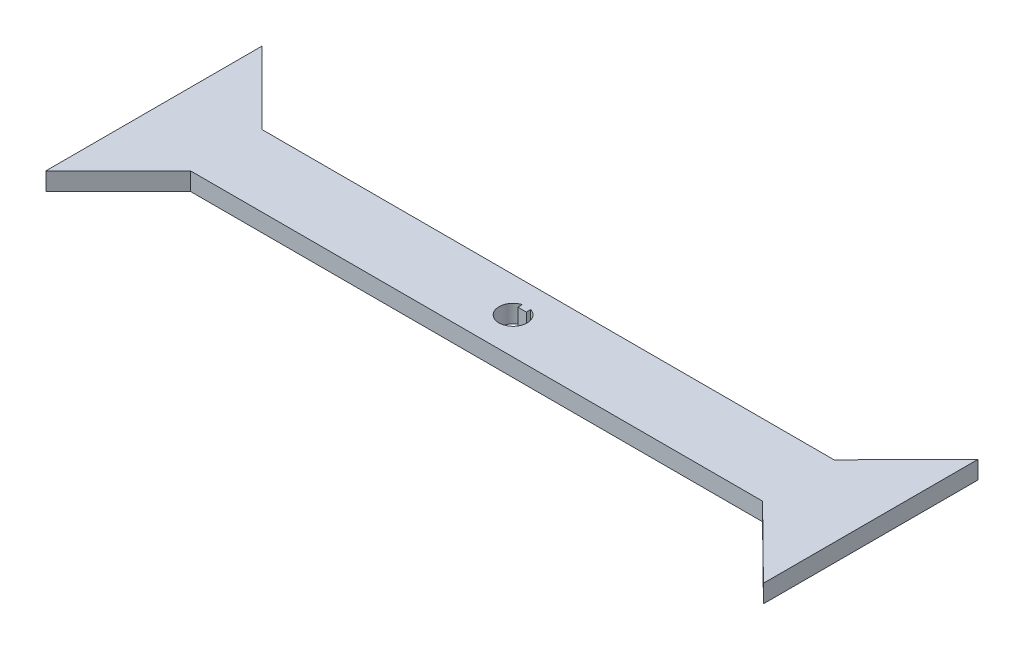
SolidWorks part; units mm, degrees
ref_plane "Front Plane" through (0, 0, 0) normal (0, 0, 1) x (1, 0, 0)
ref_plane "Top Plane" through (0, 0, 0) normal (0, 1, 0) x (1, 0, 0)
ref_plane "Right Plane" through (0, 0, 0) normal (1, 0, 0) x (0, 0, -1)
sketch "Sketch1" plane through (0, 0, 0) normal (0, 1, 0) x (1, 0, 0)
  line L0 (0, 25.4) -> (0, 51.0293)
  line L2 (0, 0) -> (0, 25.4)
  line L4 (254.2293, 0.3053) -> (254.2293, 25.7053)
  line L5 (0, 51.0293) -> (25.6293, 25.4)
  line L6 (0, 0) -> (0, -25.6293)
  line L7 (0, -25.6293) -> (25.6293, 0)
  line L8 (254.2293, 25.7053) -> (254.2293, 51.1053)
  line L9 (254.2293, 51.1053) -> (228.8293, 25.4)
  line L10 (254.2293, 0.3053) -> (254.2293, -25.0947)
  line L11 (254.2293, -25.0947) -> (228.8293, 0)
  line L12 (25.6293, 0) -> (228.8293, 0)
  line L13 (25.6293, 25.4) -> (228.8293, 25.4)
  line L15 (127.2293, 16.2053) -> (128.7293, 16.2053)
  line L16 (127.2293, 16.2053) -> (125.7293, 16.2053)
  line L17 (125.7293, 16.2053) -> (125.7293, 17.775)
  line L18 (128.7293, 16.2053) -> (128.7293, 17.775)
  circle A1 centre (127.2293, 13.0053) radius 5
  point P5 (0, 0)
  dimension "D1" = 25.4
  dimension "D16" = 10
  dimension "D2" = 254.2293
  dimension "D3" = 3
  dimension "D4" = 3.2
  dimension "D5" = 135
  dimension "D6" = 135
  dimension "D7" = 25.6293
  dimension "D8" = 25.6293
  dimension "D9" = 25.6293
  dimension "D10" = 0
  dimension "D11" = 315.342
  dimension "D12" = 25.4
  dimension "D13" = 25.4
  dimension "D14" = 35.7058
  dimension "D15" = 13.0053
  dimension "D17" = 127.2293
  dimension "D18" = 1.5
  dimension "D19" = 3.2
  dimension "D20" = 18.0688
  dimension "D21" = 17.8529
extrude "Boss-Extrude2" add sketch "Sketch1" along normal blind 6.35 contours L18 A1 L17 L16 L15 | L13 L5 L0 L2 L6 L7 L12 L11 L10 L4 L8 L9 A1
